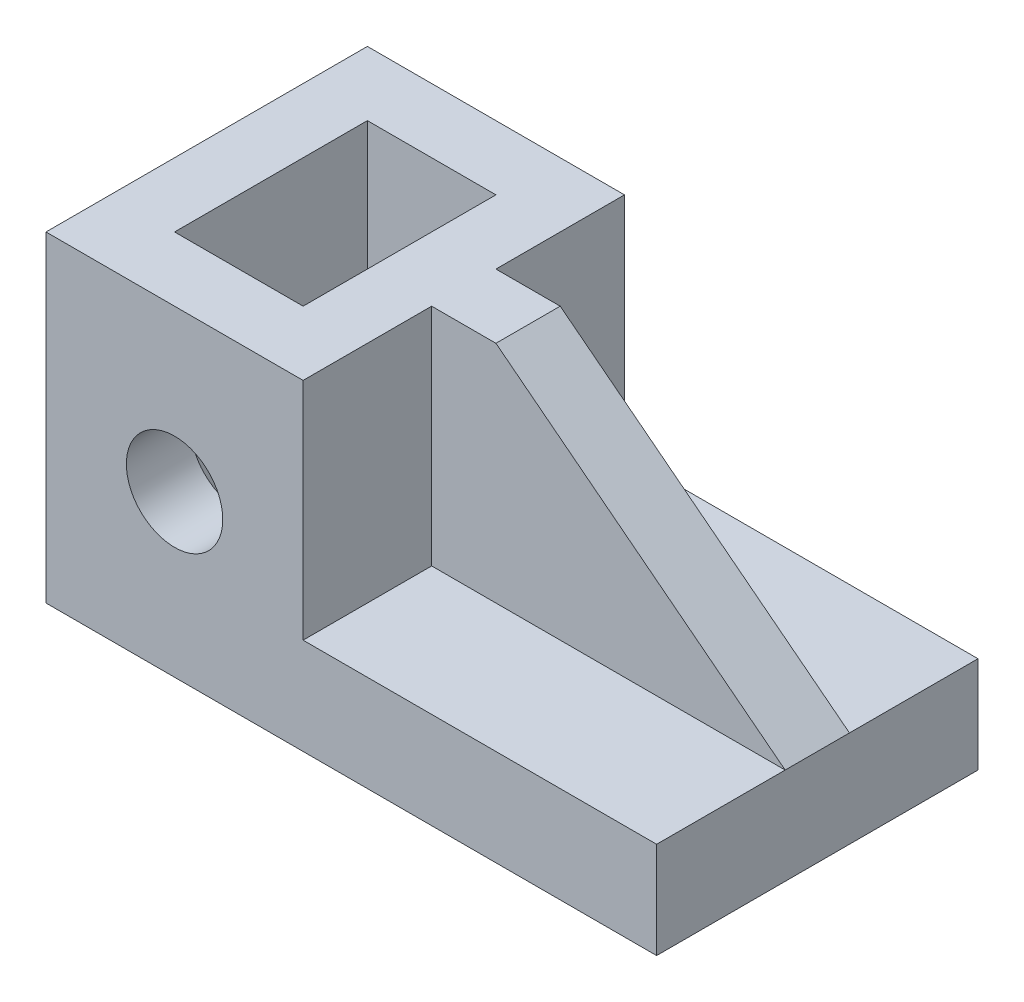
SolidWorks part; units mm, degrees
ref_plane "Front Plane" through (0, 0, 0) normal (0, 0, 1) x (1, 0, 0)
ref_plane "Top Plane" through (0, 0, 0) normal (0, 1, 0) x (1, 0, 0)
ref_plane "Right Plane" through (0, 0, 0) normal (1, 0, 0) x (0, 0, -1)
sketch "Sketch1" plane through (0, 0, 0) normal (0, 0, 1) x (1, 0, 0)
  line L0 (-7.5, 25) -> (-7.5, -10)
  line L1 (-47.5, 25) -> (-7.5, 25)
  line L2 (-47.5, 25) -> (-47.5, -25)
  line L3 (-47.5, -25) -> (47.5, -25)
  line L4 (47.5, -10) -> (47.5, -25)
  line L5 (-7.5, -10) -> (47.5, -10)
  line L7 (-47.5, -10) -> (47.5, -10) construction
  line L8 (-7.5, 25) -> (-7.5, -25) construction
  point P0 (0, 0)
  dimension "D1" = 47.5
  dimension "D2" = 47.5
  dimension "D3" = 25
  dimension "D4" = 25
  dimension "D5" = 40
  dimension "D6" = 15
extrude "Boss-Extrude1" add sketch "Sketch1" against normal blind 50
sketch "Sketch2" plane through (0, 25, 0) normal (0, 1, 0) x (1, 0, 0)
  line L0 (-7.5, 50) -> (-47.5, 50) construction
  line L1 (-37.5, 40) -> (-17.5, 40)
  line L2 (-37.5, 40) -> (-37.5, 10)
  line L3 (-37.5, 10) -> (-17.5, 10)
  line L4 (-17.5, 40) -> (-17.5, 10)
  line L7 (-7.5, 50) -> (-7.5, 0) construction
  line L8 (-47.5, 50) -> (-47.5, 0) construction
  point P11 (0, 0)
  dimension "D1" = 30
  dimension "D2" = 10
  dimension "D3" = 10
  dimension "D4" = 10
extrude "Cut-Extrude1" cut sketch "Sketch2" against normal blind 50
sketch "Sketch3" plane through (0, 0, 0) normal (0, 0, 1) x (1, 0, 0)
  line L0 (-47.5, -25) -> (47.5, -25) construction
  line L1 (-47.5, 25) -> (-47.5, -25) construction
  circle A0 centre (-27.5, 0) radius 7.5
  dimension "D3" = 15
  dimension "D1" = 25
  dimension "D2" = 20
extrude "Cut-Extrude2" cut sketch "Sketch3" against normal blind 50
sketch "Sketch4" plane through (0, 25, 0) normal (0, 1, 0) x (1, 0, 0)
  line L0 (-7.5, 50) -> (-7.5, 0) construction
  line L1 (2.5, 30) -> (-7.5, 30)
  line L2 (2.5, 30) -> (2.5, 20)
  line L3 (2.5, 20) -> (-7.5, 20)
  line L5 (-7.5, 50) -> (-7.5, 0) construction
  line L8 (47.5, 50) -> (-7.5, 50) construction
  line L10 (-17.5, 10) -> (-17.5, 40) construction
  line L11 (-37.5, 10) -> (-17.5, 10) construction
  line L13 (-7.5, 30) -> (-7.5, 20)
  point P0 (-2.457, 25)
  dimension "D1" = 10
  dimension "D2" = 10
  dimension "D3" = 25
  dimension "D4" = 10
  dimension "D5" = 10
  dimension "D7" = 30
extrude "Boss-Extrude2" add sketch "Sketch4" against normal blind 40 contours L3 L13 L1 L2
sketch "Sketch7" plane through (0, 0, -20) normal (0, 0, 1) x (1, 0, 0)
  line L0 (2.5, 25) -> (47.5, -10)
extrude "Extrude-Thin1" add sketch "Sketch7" against normal blind 10 thin
sketch "Sketch8" plane through (0, 0, -20) normal (0, 0, 1) x (1, 0, 0)
  line L0 (2.5, -10) -> (2.5, 12.3314)
  line L1 (2.5, 12.3314) -> (31.2118, -10)
  line L2 (31.2118, -10) -> (2.5, -10)
extrude "Boss-Extrude3" add sketch "Sketch8" against normal blind 10
